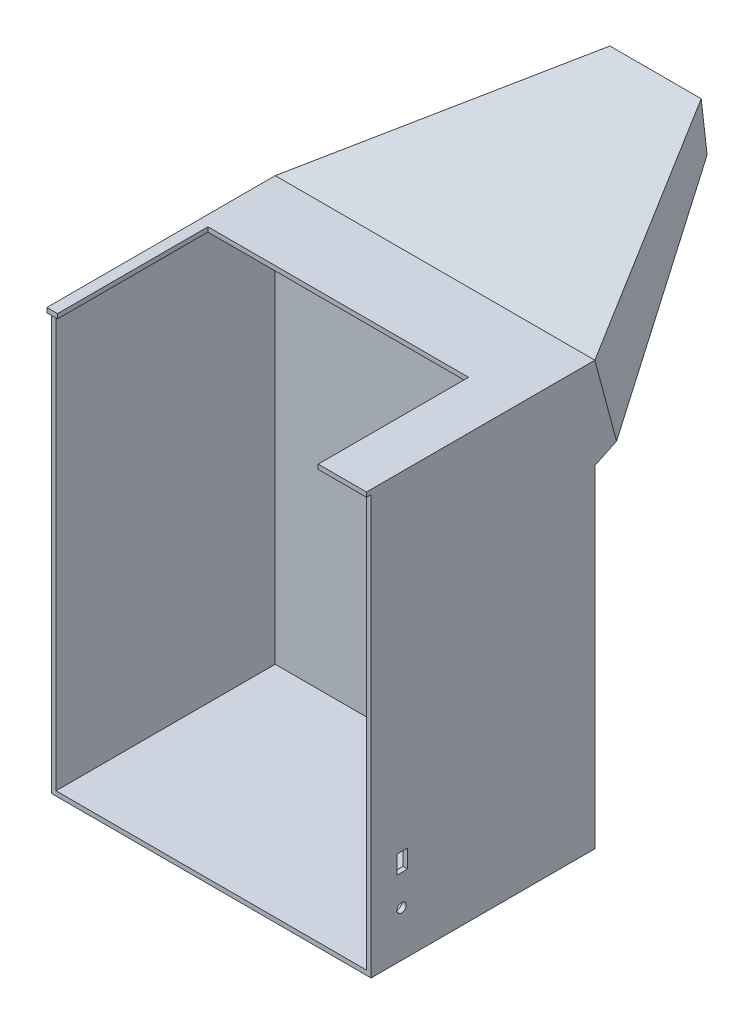
SolidWorks part; units mm, degrees
ref_plane "Front Plane" through (0, 0, 0) normal (0, 0, 1) x (1, 0, 0)
ref_plane "Top Plane" through (0, 0, 0) normal (0, 1, 0) x (1, 0, 0)
ref_plane "Right Plane" through (0, 0, 0) normal (1, 0, 0) x (0, 0, -1)
sketch "Sketch2" plane through (0, 0, 0) normal (0, 1, 0) x (1, 0, 0)
  line L1 (-55.1888, 87.4251) -> (154.8112, 87.4251)
  line L2 (-55.1888, 87.4251) -> (-55.1888, -62.5749)
  line L3 (-55.1888, -62.5749) -> (154.8112, -62.5749)
  line L4 (154.8112, 87.4251) -> (154.8112, -62.5749)
extrude "Boss-Extrude3" add sketch "Sketch2" along normal blind 275
sketch "Sketch5" plane through (0, 275, 0) normal (0, 1, 0) x (1, 0, 0)
  line L0 (-55.1888, 87.4251) -> (-55.1888, -62.5749) construction
  line L1 (-52.1888, 84.4251) -> (151.8112, 84.4251)
  line L2 (-52.1888, 84.4251) -> (-52.1888, -59.5749)
  line L3 (-52.1888, -59.5749) -> (151.8112, -59.5749)
  line L4 (151.8112, 84.4251) -> (151.8112, -59.5749)
  line L5 (154.8112, -62.5749) -> (154.8112, 87.4251) construction
  line L6 (154.8112, 87.4251) -> (-55.1888, 87.4251) construction
  line L7 (-55.1888, -62.5749) -> (154.8112, -62.5749) construction
  dimension "D1" = 3
  dimension "D2" = 3
  dimension "D3" = 3
  dimension "D4" = 3
extrude "Cut-Extrude1" cut sketch "Sketch5" against normal blind 272
sketch "Sketch6" plane through (0, 0, 62.5749) normal (0, 0, 1) x (1, 0, 0)
  line L1 (-55.1888, 275) -> (154.8112, 275)
  line L2 (-55.1888, 275) -> (-55.1888, 0)
  line L3 (-55.1888, 0) -> (154.8112, 0)
  line L4 (154.8112, 275) -> (154.8112, 0)
extrude "Cut-Extrude2" cut sketch "Sketch6" against normal blind 3
sketch "Sketch8" plane through (0, 275, 0) normal (0, 1, 0) x (1, 0, 0)
  line L0 (-55.1888, 87.4251) -> (-55.1888, -59.5749) construction
  line L1 (154.8112, -62.5749) -> (123.0635, -62.5749)
  line L2 (154.8112, -62.5749) -> (154.8112, 87.4251)
  line L3 (154.8112, 87.4251) -> (-55.1888, 87.4251)
  line L4 (-55.1888, -62.5749) -> (-55.1888, 87.4251)
  line L5 (154.8112, 87.4251) -> (-55.1888, 87.4251) construction
  line L6 (123.0635, 36.2308) -> (123.0635, -62.5749)
  line L8 (123.0635, 36.2308) -> (-48.1888, 36.2308)
  line L9 (-48.1888, -45.5749) -> (-48.1888, 69.4251) construction
  line L10 (-48.1888, 36.2308) -> (-48.1888, -62.5749)
  line L11 (-48.1888, -62.5749) -> (-55.1888, -62.5749)
extrude "Boss-Extrude4" add sketch "Sketch8" along normal blind 3
ref_plane "Plane1" through (0, 237.5212, 63.6436) normal (0, 0.9659, 0.2588) x (-1, 0, 0)
sketch "Sketch10" plane through (154.8112, 0, 0) normal (1, 0, 0) x (0, 0, -1)
  line L0 (87.4251, 278) -> (232.314, 316.8229)
  line L1 (74.9553, 274.6587) -> (-202.2426, 200.3838) construction
  line L2 (232.314, 316.8229) -> (232.314, 286.8229)
  line L3 (232.314, 286.8229) -> (87.4251, 218)
  line L4 (87.4251, 278) -> (87.4251, 0) construction
  line L5 (87.4251, 278) -> (87.4251, 218) construction
  line L6 (87.4251, 278) -> (87.4251, 218)
extrude "Boss-Extrude6" add sketch "Sketch10" against normal up to surface (210 mm away) up to face at (-55.1888, 184.3333, 11.5749)
sketch "Sketch11" plane through (0, 237.5212, 63.6436) normal (0, 0.9659, 0.2588) x (-1, 0, 0)
  line L0 (-49.8112, -156.3979) -> (-49.8112, -456.3979) construction
  line L1 (-154.8112, -156.3979) -> (55.1888, -156.3979) construction
  line L3 (55.1888, -306.3979) -> (-154.8112, -306.3979) construction
  line L4 (-19.8112, -306.3979) -> (55.1888, -156.3979)
  line L5 (55.1888, -156.3979) -> (55.1888, -306.3979)
  line L6 (55.1888, -156.3979) -> (55.1888, -306.3979) construction
  line L7 (55.1888, -306.3979) -> (-19.8112, -306.3979)
  line L8 (-79.8112, -306.3979) -> (-154.8112, -156.3979)
  line L9 (-154.8112, -156.3979) -> (-154.8112, -306.3979)
  line L10 (-154.8112, -306.3979) -> (-79.8112, -306.3979)
  point P9 (-49.8112, -306.3979)
extrude "Cut-Extrude3" cut sketch "Sketch11" against normal blind 210
sketch "Sketch12" plane through (154.8112, 0, 0) normal (1, 0, 0) x (0, 0, -1)
  line L0 (-59.5749, 0) -> (-59.5749, 275) construction
  line L1 (-59.5749, 0) -> (87.4251, 0) construction
  line L3 (-42.5749, 62) -> (-35.5749, 62)
  line L4 (-42.5749, 62) -> (-42.5749, 50)
  line L5 (-42.5749, 50) -> (-35.5749, 50)
  line L6 (-35.5749, 62) -> (-35.5749, 50)
  circle A0 centre (-39.5749, 30) radius 3
  point P10 (-39.0749, 50)
  dimension "D1" = 20
  dimension "D2" = 30
  dimension "D3" = 17
  dimension "D4" = 12
  dimension "D5" = 50
  dimension "D6" = 7
extrude "Cut-Extrude4" cut sketch "Sketch12" against normal blind 26
